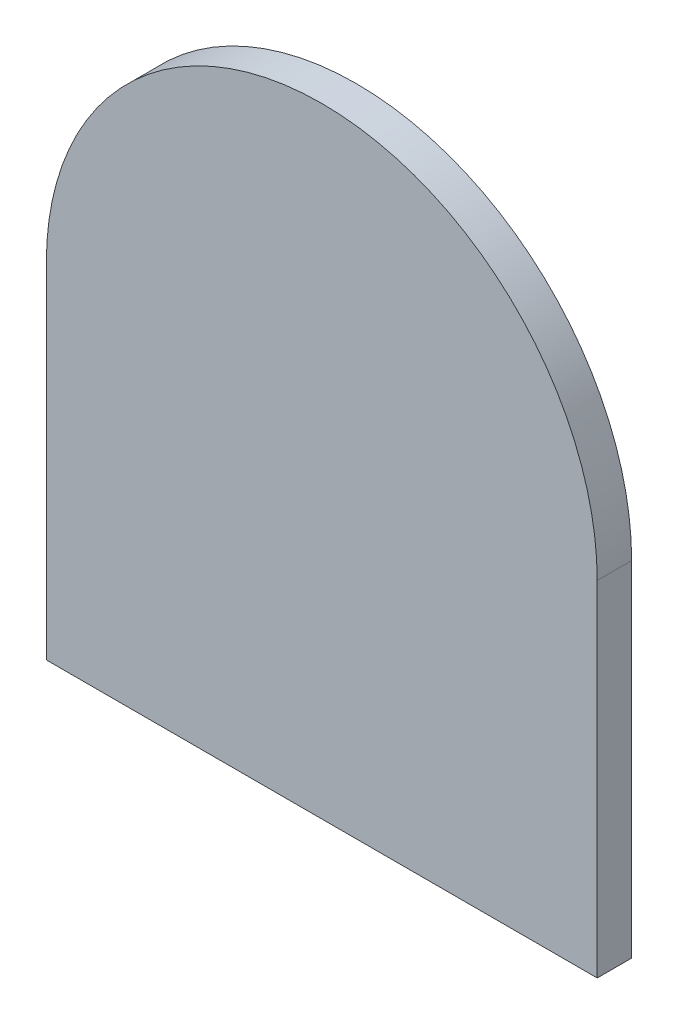
SolidWorks part; units mm, degrees
material "Plain Carbon Steel"
ref_plane "Front Plane" through (0, 0, 0) normal (0, 0, 1) x (1, 0, 0)
ref_plane "Top Plane" through (0, 0, 0) normal (0, 1, 0) x (1, 0, 0)
ref_plane "Right Plane" through (0, 0, 0) normal (1, 0, 0) x (0, 0, -1)
sketch "Sketch1" plane through (0, 0, 0) normal (0, 0, 1) x (1, 0, 0)
  line L0 (0, 0) -> (0, 317.5)
  line L1 (-254, 317.5) -> (-254, 0)
  line L2 (-254, 0) -> (254, 0)
  line L3 (254, 0) -> (254, 317.5)
  circle A0 centre (0, 317.5) radius 254
  dimension "D2" = 508
  dimension "D1" = 317.5
extrude "Boss-Extrude1" add sketch "Sketch1" against normal blind 31.75
sketch "Sketch2" plane through (0, 0, 0) normal (0, 0, 1) x (1, 0, 0)
  point P0 (0, 317.5)
